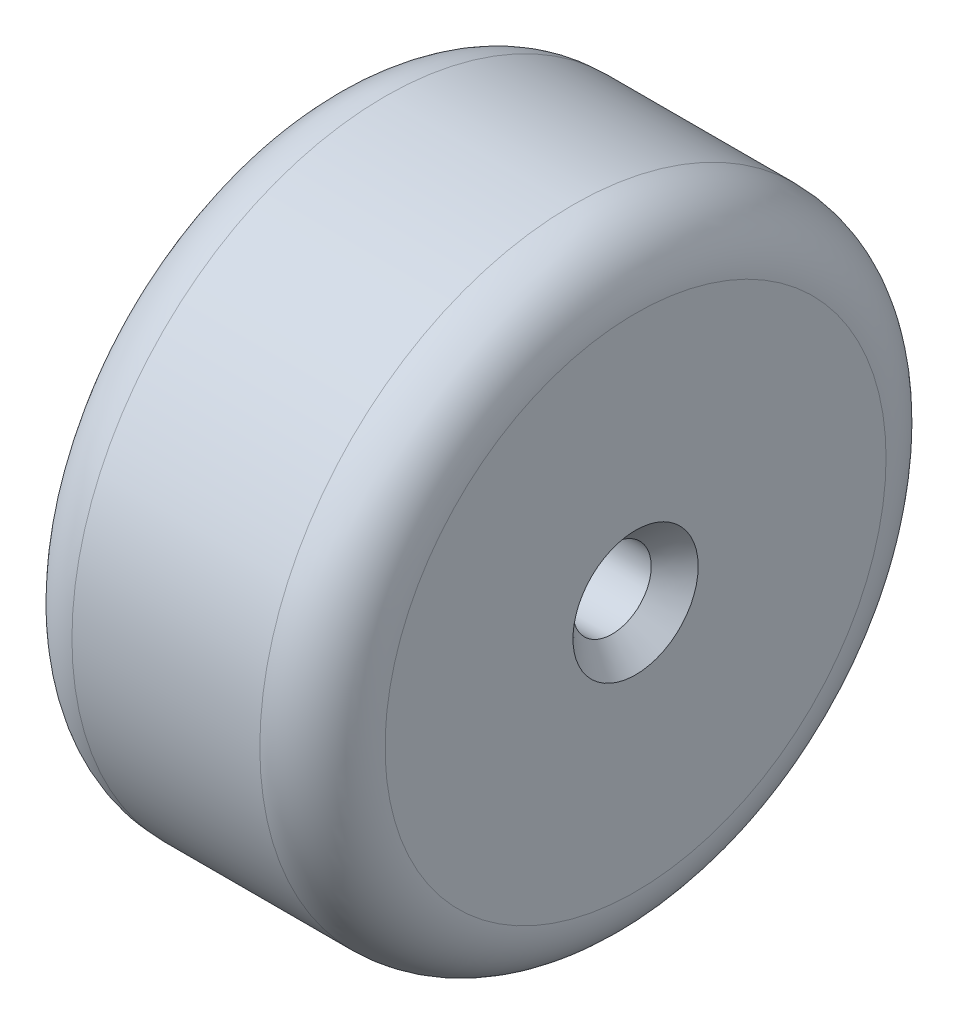
SolidWorks part; units mm, degrees
material "Natural Rubber"
ref_plane "前视基准面" through (0, 0, 0) normal (0, 0, 1) x (1, 0, 0)
ref_plane "上视基准面" through (0, 0, 0) normal (0, 1, 0) x (1, 0, 0)
ref_plane "右视基准面" through (0, 0, 0) normal (1, 0, 0) x (0, 0, -1)
sketch "Sketch1" plane through (0, 0, 0) normal (1, 0, 0) x (0, 0, -1)
  circle A0 centre (0, 0) radius 40
  dimension "D1" = 80
extrude "Boss-Extrude1" add sketch "Sketch1" along normal blind 40
fillet "Fillet1" radius 8 2 edges at (0, 0, -40) (40, 0, -40)
sketch "Sketch2" plane through (40, 0, 0) normal (1, 0, 0) x (0, 0, -1)
  circle A0 centre (0, 0) radius 5
  dimension "D1" = 10
extrude "Cut-Extrude1" cut sketch "Sketch2" against normal through all
chamfer "Chamfer1" distance 3 angle 45 2 edges at (0, 0, -5) (40, 0, -5)
